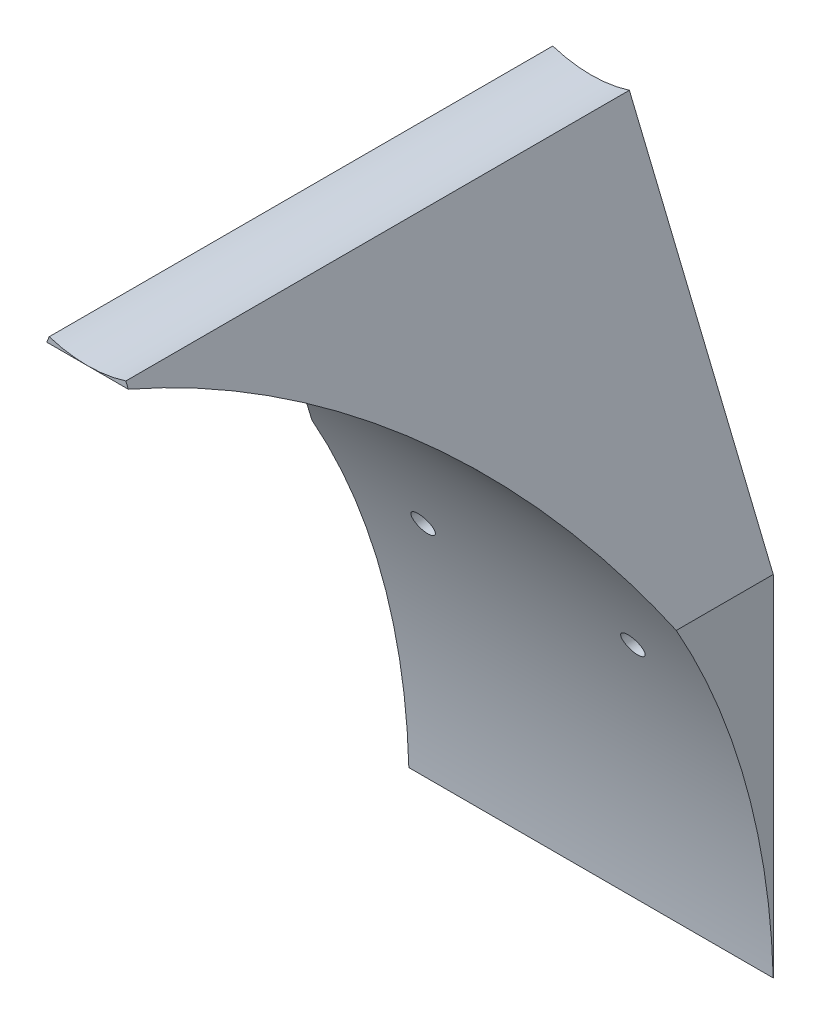
SolidWorks part; units mm, degrees
ref_plane "Front Plane" through (0, 0, 0) normal (0, 0, 1) x (1, 0, 0)
ref_plane "Top Plane" through (0, 0, 0) normal (0, 1, 0) x (1, 0, 0)
ref_plane "Right Plane" through (0, 0, 0) normal (1, 0, 0) x (0, 0, -1)
sketch "Sketch1" plane through (0, 0, 0) normal (0, 0, 1) x (1, 0, 0)
  line L0 (0, 0) -> (0, -127) construction
  line L1 (0, 0) -> (29.1605, -70.3996) construction
  line L2 (0, 0) -> (-29.1605, -70.3996) construction
  line L3 (-29.1605, -70.3996) -> (-29.1605, -123.6069) construction
  line L5 (0, 0) -> (0, -127) construction
  line L6 (29.1605, -123.6069) -> (29.1605, -70.3996) construction
  line L7 (29.1605, -123.6069) -> (29.1605, -161.7069) construction
  line L8 (-50.8, -190.8674) -> (0, -190.8674) construction
  line L9 (-50.8, -189.2799) -> (0, -189.2799) construction
  line L10 (27.573, -123.6069) -> (27.573, -161.7069) construction
  line L11 (27.573, -123.6069) -> (27.573, -70.7154)
  line L12 (0, -4.1483) -> (27.573, -70.7154)
  line L13 (0, -4.1483) -> (-27.573, -70.7154)
  line L14 (-27.573, -70.7154) -> (-27.573, -123.6069)
  line L15 (-27.573, -123.6069) -> (-29.1605, -123.6069) construction
  line L16 (-50.8, -189.2799) -> (-50.8, -190.8674) construction
  line L17 (27.573, -123.6069) -> (-27.573, -123.6069)
  circle A0 centre (0, 0) radius 127 construction
  circle A1 centre (0, 0) radius 76.2 construction
  arc A2 (29.1605, -161.7069) -> (0, -190.8674) centre (0, -161.7069) cw construction
  arc A3 (27.573, -161.7069) -> (0, -189.2799) centre (0, -161.7069) cw construction
  point P2 (-15.875, -74.528)
  point P12 (0, 0)
  point P14 (15.875, -74.528)
  point P25 (0, -38.1)
  dimension "D2" = 152.4
  dimension "D6" = 1.5875
  dimension "D1" = 127
  dimension "D3" = 38.1
  dimension "D4" = 50.8
  dimension "D5" = 45
  dimension "D7" = 38.1
  dimension "D8" = 31.75
extrude "Boss-Extrude1" add sketch "Sketch1" along normal blind 76.2
sketch "Sketch2" plane through (0, 0, 0) normal (1, 0, 0) x (0, 0, -1)
  line L3 (-76.2, -123.6069) -> (0, -123.6069) construction
  line L4 (-76.2, -123.6069) -> (-76.2, -70.7154) construction
  line L5 (-76.2, -70.7154) -> (-76.2, -4.1483) construction
  line L6 (-76.2, -123.6069) -> (0, -123.6069)
  line L7 (-76.2, -123.6069) -> (-76.2, -70.7154)
  line L8 (-76.2, -70.7154) -> (-76.2, -19.05)
  arc A0 (-76.2, -19.05) -> (0, -123.6069) centre (-114.2546, -126.8291) cw
  point P2 (-0.4307, -123.6069)
  point P5 (-63.5, -22.7889)
  point P6 (0, 0)
  point P9 (0, -123.6069)
  dimension "D1" = 19.05
  dimension "D2" = 114.3
extrude "Cut-Extrude1" cut sketch "Sketch2" along normal up to surface (55.146 mm away) from surface
sketch "Sketch5" plane through (0, 0, 0) normal (0, 0, 1) x (1, 0, 0)
  line L0 (0, -82.55) -> (0, 0) construction
  circle A0 centre (0, 0) radius 82.55 construction
  point P0 (0, -38.1)
  point P4 (-15.875, -81.0092)
  point P5 (15.875, -81.0092)
  point P7 (0, 0)
  point P8 (0, 0)
  point P9 (0, 0)
  dimension "D1" = 38.1
  dimension "D3" = 165.1
  dimension "D2" = 31.75
hole_wizard "M3 Clearance Hole1" positions "Sketch7" profile "Sketch8" hole size "M3" standard "ANSI Metric" end condition through all
sketch "Sketch7" plane through (0, 0, 0) normal (0, 0, -1) x (-1, 0, 0)
  point P0 (-15.875, -81.0092)
  point P3 (15.875, -81.0092)
  point P6 (0, -38.1)
sketch "Sketch8" plane through (15.875, -81.0092, 0) normal (1, 0, 0) x (0, 1, 0)
  line L0 (0, 0) -> (0, 76.2)
  line L1 (0, 76.2) -> (1.7, 76.2)
  line L2 (1.7, 76.2) -> (1.7, 0)
  line L5 (1.7, 0) -> (0, 0)
  line L11 (0, -6.35) -> (0, 107.95) construction
  dimension "Thru Hole Dia." = 3.4
  dimension "Thru Hole Depth" = 76.2
sketch "Sketch10" plane through (0, 0, 0) normal (0, 0, -1) x (-1, 0, 0)
  circle A0 centre (0, 0) radius 19.05
  dimension "D1" = 38.1
extrude "Cut-Extrude2" cut sketch "Sketch10" against normal up to next
